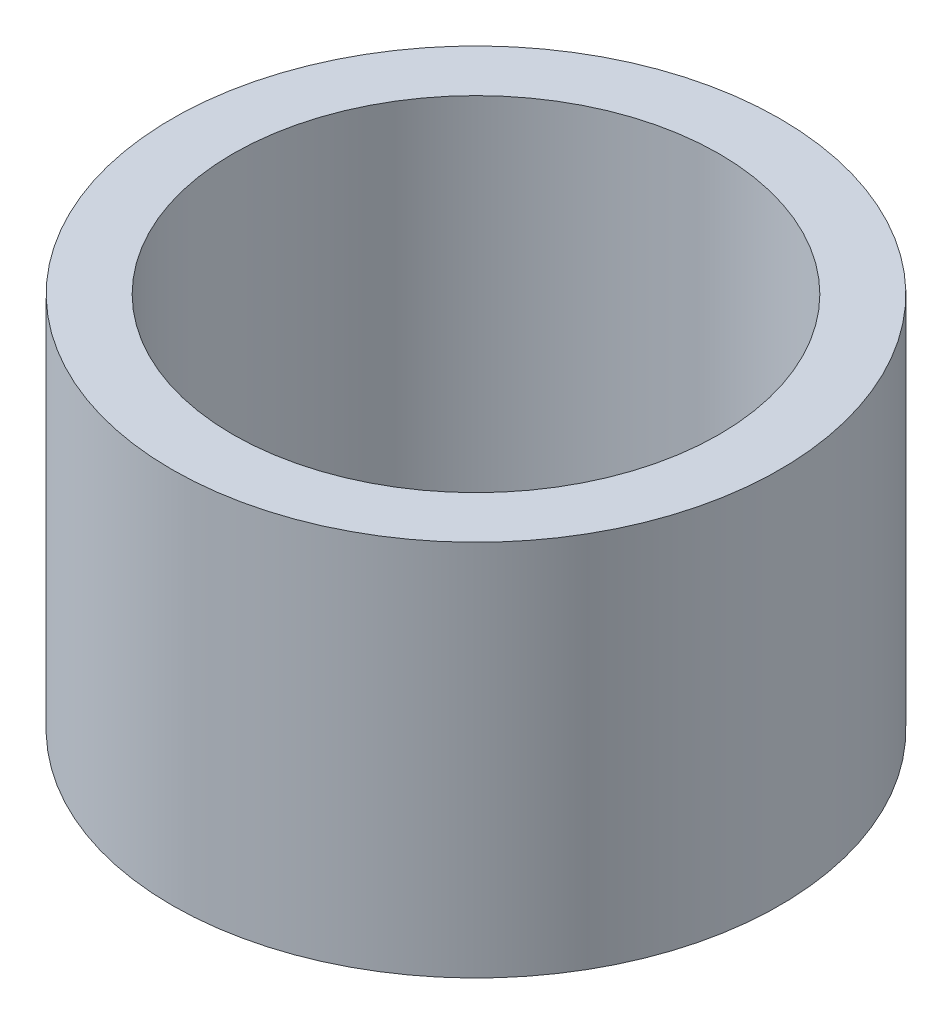
SolidWorks part; units mm, degrees
ref_plane "Front Plane" through (0, 0, 0) normal (0, 0, 1) x (1, 0, 0)
ref_plane "Top Plane" through (0, 0, 0) normal (0, 1, 0) x (1, 0, 0)
ref_plane "Right Plane" through (0, 0, 0) normal (1, 0, 0) x (0, 0, -1)
sketch "Sketch1" plane through (0, 0, 0) normal (0, 1, 0) x (1, 0, 0)
  circle A0 centre (0, 0) radius 31.75
  circle A1 centre (0, 0) radius 25.4
  dimension "D1" = 63.5
  dimension "D2" = 50.8
extrude "Boss-Extrude1" add sketch "Sketch1" along normal mid plane 39.4208
